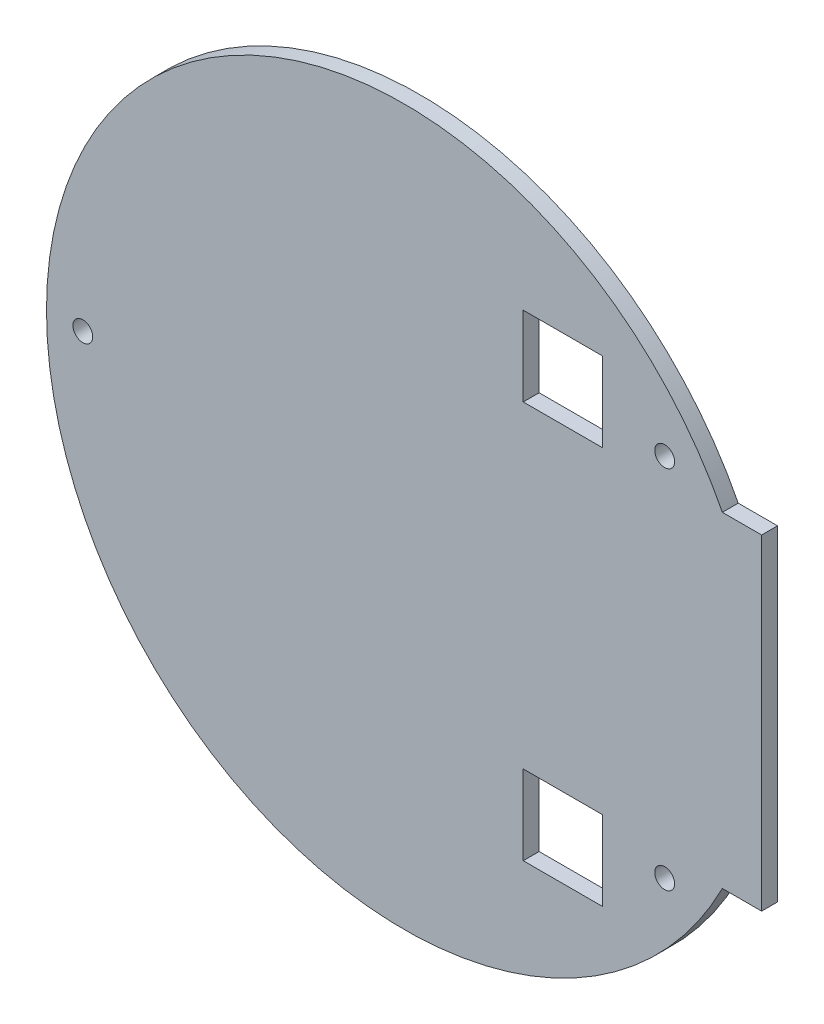
SolidWorks part; units mm, degrees
ref_plane "Front Plane" through (0, 0, 0) normal (0, 0, 1) x (1, 0, 0)
ref_plane "Top Plane" through (0, 0, 0) normal (0, 1, 0) x (1, 0, 0)
ref_plane "Right Plane" through (0, 0, 0) normal (1, 0, 0) x (0, 0, -1)
sketch "Sketch1" plane through (0, 0, 0) normal (0, 0, 1) x (1, 0, 0)
  line L0 (45, 20.5) -> (40.0593, 20.5) construction
  line L1 (45, -20.5) -> (45, 20.5) construction
  line L2 (40.0593, -20.5) -> (45, -20.5) construction
  line L3 (45, 20.5) -> (40.0593, 20.5)
  line L4 (45, -20.5) -> (45, 20.5)
  line L5 (40.0593, -20.5) -> (45, -20.5)
  line L6 (-1000, 0) -> (49000, 0) construction
  line L7 (25, 20) -> (15, 20)
  line L8 (25, 20) -> (25, 30)
  line L9 (25, 30) -> (15, 30)
  line L10 (15, 20) -> (15, 30)
  line L11 (25, 20) -> (15, 30) construction
  line L12 (25, 30) -> (15, 20) construction
  line L13 (25, -30) -> (15, -20) construction
  line L14 (25, -20) -> (15, -30) construction
  line L15 (15, -20) -> (15, -30)
  line L16 (25, -30) -> (15, -30)
  line L17 (25, -20) -> (25, -30)
  line L18 (25, -20) -> (15, -20)
  circle A2 centre (-40.4273, 0) radius 1.25
  circle A4 centre (32.7988, -23) radius 1.25
  arc A5 (40.0593, 20.5) -> (40.0593, -20.5) centre (0, 0) ccw construction
  circle A6 centre (32.7988, 23) radius 1.25
  arc A7 (40.0593, 20.5) -> (40.0593, -20.5) centre (0, 0) ccw
  point P3 (0, 0)
  point P13 (20, 25)
  point P25 (20, -25)
  dimension "D1" = 2.5
  dimension "D3" = 10
  dimension "D4" = 10
  dimension "D5" = 20
  dimension "D6" = 25
extrude "Body" add sketch "Sketch1" along normal blind 2
